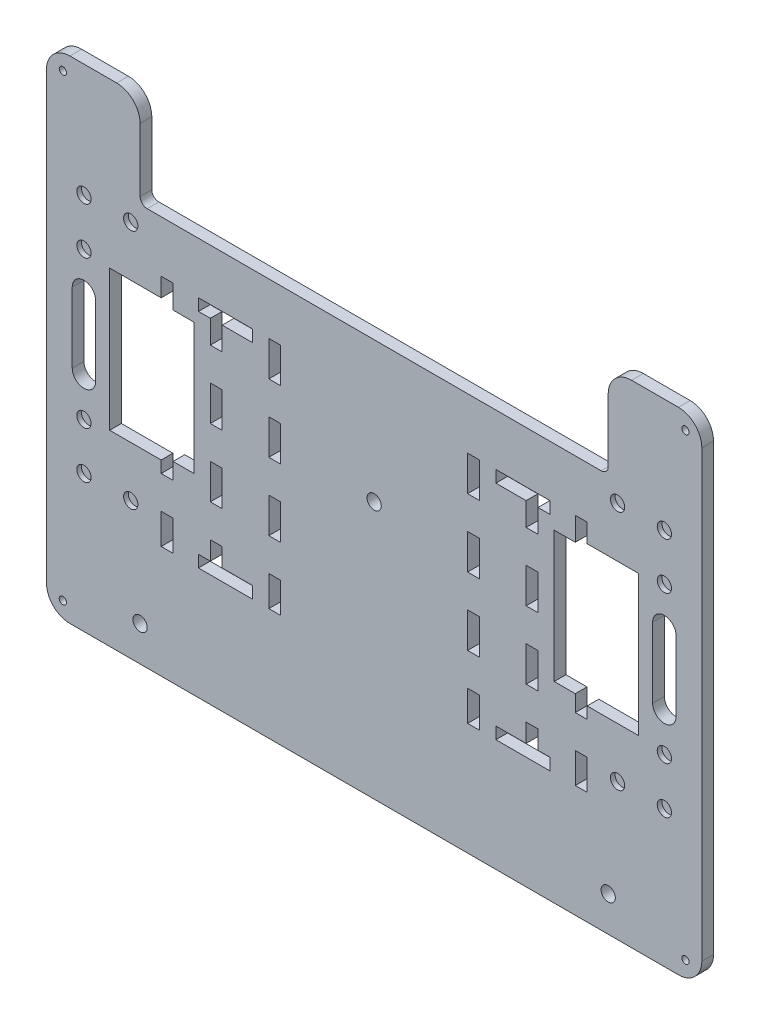
SolidWorks part; units mm, degrees
material "Acrylique (impact moyen-haut)"
ref_plane "Plan de face" through (0, 0, 0) normal (0, 0, 1) x (1, 0, 0)
ref_plane "Plan de dessus" through (0, 0, 0) normal (0, 1, 0) x (1, 0, 0)
ref_plane "Plan de droite" through (0, 0, 0) normal (1, 0, 0) x (0, 0, -1)
sketch "Esquisse1" plane through (0, 0, 0) normal (0, 0, 1) x (1, 0, 0)
  line L1 (130, -105) -> (-130, -105)
  line L2 (140, -95) -> (140, 105)
  line L3 (140, 105) -> (-140, 105)
  line L4 (-140, -95) -> (-140, 105)
  line L5 (140, -105) -> (-140, 105) construction
  line L6 (140, 105) -> (-140, -105) construction
  arc A0 (130, -105) -> (140, -95) centre (130, -95) ccw
  arc A1 (-130, -105) -> (-140, -95) centre (-130, -95) cw
  point P0 (0, 0)
  dimension "D3" = 10
  dimension "D1" = 210
  dimension "D2" = 280
extrude "Boss.-Extru.1" add sketch "Esquisse1" along normal blind 5
sketch "Esquisse2" plane through (0, 0, 5) normal (0, 0, 1) x (1, 0, 0)
  line L0 (-85.93, -1) -> (-91, -1)
  line L1 (-85.93, 28) -> (-91, 28)
  line L2 (-85.93, 28) -> (-85.93, 43)
  line L3 (-85.93, 43) -> (-91, 43)
  line L4 (-91, 28) -> (-91, 43)
  line L5 (-85.93, 28) -> (-91, 43) construction
  line L6 (-85.93, 43) -> (-91, 28) construction
  line L7 (-85.93, -1) -> (-85.93, 14)
  line L8 (-85.93, 14) -> (-91, 14)
  line L9 (-91, -1) -> (-91, 14)
  line L10 (-85.93, -1) -> (-91, 14) construction
  line L11 (-85.93, 14) -> (-91, -1) construction
  line L12 (-85.93, -57) -> (-91, -57)
  line L13 (-85.93, -30) -> (-91, -30)
  line L14 (-85.93, -30) -> (-85.93, -15)
  line L15 (-85.93, -15) -> (-91, -15)
  line L16 (-91, -30) -> (-91, -15)
  line L17 (-85.93, -30) -> (-91, -15) construction
  line L18 (-85.93, -15) -> (-91, -30) construction
  line L19 (-85.93, -57) -> (-85.93, -44)
  line L20 (-85.93, -44) -> (-91, -44)
  line L21 (-91, -57) -> (-91, -44)
  line L22 (-85.93, -57) -> (-91, -44) construction
  line L23 (-85.93, -44) -> (-91, -57) construction
  line L26 (-64.93, -1) -> (-70, -1)
  line L27 (-64.93, 28) -> (-70, 28)
  line L28 (-64.93, 28) -> (-64.93, 43)
  line L29 (-64.93, 43) -> (-70, 43)
  line L30 (-70, 28) -> (-70, 43)
  line L31 (-64.93, 28) -> (-70, 43) construction
  line L32 (-64.93, 43) -> (-70, 28) construction
  line L33 (-64.93, -1) -> (-64.93, 14)
  line L34 (-64.93, 14) -> (-70, 14)
  line L35 (-70, -1) -> (-70, 14)
  line L36 (-64.93, -1) -> (-70, 14) construction
  line L37 (-64.93, 14) -> (-70, -1) construction
  line L38 (-64.93, -57) -> (-70, -57)
  line L39 (-64.93, -30) -> (-70, -30)
  line L40 (-64.93, -30) -> (-64.93, -15)
  line L41 (-64.93, -15) -> (-70, -15)
  line L42 (-70, -30) -> (-70, -15)
  line L43 (-64.93, -30) -> (-70, -15) construction
  line L44 (-64.93, -15) -> (-70, -30) construction
  line L45 (-64.93, -57) -> (-64.93, -44)
  line L46 (-64.93, -44) -> (-70, -44)
  line L47 (-70, -57) -> (-70, -44)
  line L48 (-64.93, -57) -> (-70, -44) construction
  line L49 (-64.93, -44) -> (-70, -57) construction
  line L50 (-39.93, -1) -> (-45, -1)
  line L51 (-39.93, 28) -> (-45, 28)
  line L52 (-39.93, 28) -> (-39.93, 43)
  line L53 (-39.93, 43) -> (-45, 43)
  line L54 (-45, 28) -> (-45, 43)
  line L55 (-39.93, 28) -> (-45, 43) construction
  line L56 (-39.93, 43) -> (-45, 28) construction
  line L57 (-39.93, -1) -> (-39.93, 14)
  line L58 (-39.93, 14) -> (-45, 14)
  line L59 (-45, -1) -> (-45, 14)
  line L60 (-39.93, -1) -> (-45, 14) construction
  line L61 (-39.93, 14) -> (-45, -1) construction
  line L62 (-39.93, -57) -> (-45, -57)
  line L63 (-39.93, -30) -> (-45, -30)
  line L64 (-39.93, -30) -> (-39.93, -15)
  line L65 (-39.93, -15) -> (-45, -15)
  line L66 (-45, -30) -> (-45, -15)
  line L67 (-39.93, -30) -> (-45, -15) construction
  line L68 (-39.93, -15) -> (-45, -30) construction
  line L69 (-39.93, -57) -> (-39.93, -44)
  line L70 (-39.93, -44) -> (-45, -44)
  line L71 (-45, -57) -> (-45, -44)
  line L72 (-39.93, -57) -> (-45, -44) construction
  line L73 (-39.93, -44) -> (-45, -57) construction
  line L74 (0, 0) -> (0, 77.3847) construction
  line L75 (-75.07, 43) -> (-52, 43)
  line L76 (-75.07, 43) -> (-75.07, 37.93)
  line L77 (-75.07, 37.93) -> (-52, 37.93)
  line L78 (-52, 43) -> (-52, 37.93)
  line L79 (-75.07, -57) -> (-52, -57)
  line L80 (-75.07, -57) -> (-75.07, -51.93)
  line L81 (-75.07, -51.93) -> (-52, -51.93)
  line L82 (-52, -57) -> (-52, -51.93)
  line L83 (39.93, -44) -> (45, -57) construction
  line L84 (39.93, -57) -> (45, -44) construction
  line L85 (39.93, -15) -> (45, -30) construction
  line L86 (39.93, -30) -> (45, -15) construction
  line L87 (39.93, 14) -> (45, -1) construction
  line L88 (39.93, -1) -> (45, 14) construction
  line L89 (39.93, 43) -> (45, 28) construction
  line L90 (39.93, 28) -> (45, 43) construction
  line L91 (64.93, -44) -> (70, -57) construction
  line L92 (64.93, -57) -> (70, -44) construction
  line L93 (64.93, -15) -> (70, -30) construction
  line L94 (64.93, -30) -> (70, -15) construction
  line L95 (64.93, 14) -> (70, -1) construction
  line L96 (64.93, -1) -> (70, 14) construction
  line L97 (64.93, 43) -> (70, 28) construction
  line L98 (64.93, 28) -> (70, 43) construction
  line L99 (85.93, -44) -> (91, -57) construction
  line L100 (85.93, -57) -> (91, -44) construction
  line L101 (85.93, -15) -> (91, -30) construction
  line L102 (85.93, -30) -> (91, -15) construction
  line L103 (85.93, 14) -> (91, -1) construction
  line L104 (85.93, -1) -> (91, 14) construction
  line L105 (85.93, 43) -> (91, 28) construction
  line L106 (85.93, 28) -> (91, 43) construction
  line L107 (52, -57) -> (52, -51.93)
  line L108 (75.07, -51.93) -> (52, -51.93)
  line L109 (75.07, -57) -> (75.07, -51.93)
  line L110 (75.07, -57) -> (52, -57)
  line L111 (52, 43) -> (52, 37.93)
  line L112 (75.07, 37.93) -> (52, 37.93)
  line L113 (75.07, 43) -> (75.07, 37.93)
  line L114 (75.07, 43) -> (52, 43)
  line L115 (45, -57) -> (45, -44)
  line L116 (39.93, -44) -> (45, -44)
  line L117 (39.93, -57) -> (39.93, -44)
  line L118 (45, -30) -> (45, -15)
  line L119 (39.93, -15) -> (45, -15)
  line L120 (39.93, -30) -> (39.93, -15)
  line L121 (39.93, -30) -> (45, -30)
  line L122 (39.93, -57) -> (45, -57)
  line L123 (45, -1) -> (45, 14)
  line L124 (39.93, 14) -> (45, 14)
  line L125 (39.93, -1) -> (39.93, 14)
  line L126 (45, 28) -> (45, 43)
  line L127 (39.93, 43) -> (45, 43)
  line L128 (39.93, 28) -> (39.93, 43)
  line L129 (39.93, 28) -> (45, 28)
  line L130 (39.93, -1) -> (45, -1)
  line L131 (70, -57) -> (70, -44)
  line L132 (64.93, -44) -> (70, -44)
  line L133 (64.93, -57) -> (64.93, -44)
  line L134 (70, -30) -> (70, -15)
  line L135 (64.93, -15) -> (70, -15)
  line L136 (64.93, -30) -> (64.93, -15)
  line L137 (64.93, -30) -> (70, -30)
  line L138 (64.93, -57) -> (70, -57)
  line L139 (70, -1) -> (70, 14)
  line L140 (64.93, 14) -> (70, 14)
  line L141 (64.93, -1) -> (64.93, 14)
  line L142 (70, 28) -> (70, 43)
  line L143 (64.93, 43) -> (70, 43)
  line L144 (64.93, 28) -> (64.93, 43)
  line L145 (64.93, 28) -> (70, 28)
  line L146 (64.93, -1) -> (70, -1)
  line L147 (91, -57) -> (91, -44)
  line L148 (85.93, -44) -> (91, -44)
  line L149 (85.93, -57) -> (85.93, -44)
  line L150 (91, -30) -> (91, -15)
  line L151 (85.93, -15) -> (91, -15)
  line L152 (85.93, -30) -> (85.93, -15)
  line L153 (85.93, -30) -> (91, -30)
  line L154 (85.93, -57) -> (91, -57)
  line L155 (91, -1) -> (91, 14)
  line L156 (85.93, 14) -> (91, 14)
  line L157 (85.93, -1) -> (85.93, 14)
  line L158 (91, 28) -> (91, 43)
  line L159 (85.93, 43) -> (91, 43)
  line L160 (85.93, 28) -> (85.93, 43)
  line L161 (85.93, 28) -> (91, 28)
  line L162 (85.93, -1) -> (91, -1)
  line L163 (76.93, -23) -> (85.93, 33) construction
  line L164 (-91, -25) -> (-113, -25)
  line L165 (-91, -25) -> (-91, 35)
  line L166 (-91, 35) -> (-113, 35)
  line L167 (-113, -25) -> (-113, 35)
  line L168 (-91, -25) -> (-113, 35) construction
  line L169 (-91, 35) -> (-113, -25) construction
  line L170 (-76.93, -23) -> (-85.93, -23)
  line L171 (-76.93, -23) -> (-76.93, 33)
  line L172 (-76.93, 33) -> (-85.93, 33)
  line L173 (-85.93, -23) -> (-85.93, 33)
  line L174 (-76.93, -23) -> (-85.93, 33) construction
  line L175 (-76.93, 33) -> (-85.93, -23) construction
  line L176 (76.93, 33) -> (85.93, -23) construction
  line L177 (91, 35) -> (113, -25) construction
  line L178 (91, -25) -> (113, 35) construction
  line L179 (91, 35) -> (113, 35)
  line L180 (113, -25) -> (113, 35)
  line L181 (91, -25) -> (113, -25)
  line L182 (91, -25) -> (91, 35)
  line L183 (85.93, -23) -> (85.93, 33)
  line L184 (76.93, -23) -> (85.93, -23)
  line L185 (76.93, -23) -> (76.93, 33)
  line L186 (76.93, 33) -> (85.93, 33)
  line L187 (140, 105) -> (-140, 105) construction
  line L188 (-140, 105) -> (-140, -95) construction
  point P0 (-88.465, 35.5)
  point P5 (-88.465, 6.5)
  point P10 (-88.465, -22.5)
  point P15 (-88.465, -50.5)
  point P24 (-67.465, 35.5)
  point P29 (-67.465, 6.5)
  point P34 (-67.465, -22.5)
  point P39 (-67.465, -50.5)
  point P44 (-42.465, 35.5)
  point P49 (-42.465, 6.5)
  point P54 (-42.465, -22.5)
  point P59 (-42.465, -50.5)
  point P131 (42.465, -50.5)
  point P132 (42.465, -22.5)
  point P133 (42.465, 6.5)
  point P134 (42.465, 35.5)
  point P135 (67.465, -50.5)
  point P136 (67.465, -22.5)
  point P137 (67.465, 6.5)
  point P138 (67.465, 35.5)
  point P139 (88.465, -50.5)
  point P140 (88.465, -22.5)
  point P141 (88.465, 6.5)
  point P142 (88.465, 35.5)
  point P143 (-102, 5)
  point P148 (-81.43, 5)
  point P153 (81.43, 5)
  point P158 (102, 5)
  dimension "D1" = 5.07
  dimension "D2" = 15
  dimension "D3" = 5.07
  dimension "D4" = 14
  dimension "D5" = 0
  dimension "D6" = 15
  dimension "D7" = 5.07
  dimension "D8" = 15
  dimension "D9" = 5.07
  dimension "D10" = 14
  dimension "D11" = 0
  dimension "D12" = 100
  dimension "D13" = 14
  dimension "D14" = 0
  dimension "D15" = 100
  dimension "D16" = 27
  dimension "D17" = 5.07
  dimension "D18" = 15
  dimension "D19" = 5.07
  dimension "D20" = 14
  dimension "D21" = 0
  dimension "D22" = 15
  dimension "D23" = 5.07
  dimension "D24" = 15
  dimension "D25" = 5.07
  dimension "D26" = 14
  dimension "D27" = 0
  dimension "D28" = 14
  dimension "D29" = 0
  dimension "D30" = 100
  dimension "D31" = 0
  dimension "D32" = 46
  dimension "D33" = 5.07
  dimension "D34" = 15
  dimension "D35" = 5.07
  dimension "D36" = 14
  dimension "D37" = 0
  dimension "D38" = 15
  dimension "D39" = 5.07
  dimension "D40" = 15
  dimension "D41" = 5.07
  dimension "D42" = 14
  dimension "D43" = 0
  dimension "D44" = 14
  dimension "D45" = 0
  dimension "D46" = 100
  dimension "D47" = 0
  dimension "D48" = 25
  dimension "D49" = 23.07
  dimension "D50" = 15.93
  dimension "D51" = 5.07
  dimension "D52" = 5.07
  dimension "D53" = 23.07
  dimension "D54" = 5.07
  dimension "D55" = 5.07
  dimension "D56" = 15.93
  dimension "D57" = 0
  dimension "D58" = 60
  dimension "D59" = 22
  dimension "D60" = 38
  dimension "D61" = 38
  dimension "D62" = 56
  dimension "D63" = 0
  dimension "D64" = 9
extrude "Enlèv. mat.-Extru.1" cut sketch "Esquisse2" against normal blind 10 contours L183 L156 L182 L161 | L186 L185 L184 L152 L183 L157 L160 | L160 L161 L158 L159 | L182 L150 L181 L180 L179 L158 L155 | L157 L162 L155 L156 | L152 L153 L150 L151 | L183 L151 L182 L162 | L131 L110 L109 L108 | L133 L110 L131 L108 | L110 L133 L108 L107 | L149 L154 L147 L148 | L167 L164 L16 L165 L9 L4 L166 | L9 L0 L7 L8 | L8 L173 L1 L165 | L15 L173 L0 L165 | L77 L30 L27 L28 | L116 L115 L122 L117 | L121 L118 L119 L120 | L137 L134 L135 L136 | L141 L140 L139 L146 | L123 L124 L125 L130 | L129 L126 L127 L128 | L144 L143 L142 L145 | L112 L111 L114 L113 | L20 L21 L12 L19 | L81 L82 L79 L80 | L47 L46 L45 L38 | L71 L70 L69 L62 | L66 L65 L64 L63 | L39 L42 L41 L40 | L26 L35 L34 L33 | L50 L59 L58 L57 | L51 L54 L53 L52
sketch "Esquisse3" plane through (0, 0, 5) normal (0, 0, 1) x (1, 0, 0)
  line L0 (-124, 5) -> (-31.3779, 5) construction
  line L1 (-113, -25) -> (-113, 35) construction
  line L3 (-124, 36.5) -> (-124, -26.5) construction
  line L4 (-140, 105) -> (-140, -95) construction
  line L5 (0, 0) -> (0, 65.434) construction
  line L6 (124, 36.5) -> (124, -26.5) construction
  circle A0 centre (-124, -26.5) radius 3.05
  circle A1 centre (-124, 36.5) radius 3.05
  circle A2 centre (124, 36.5) radius 3.05
  circle A3 centre (124, -26.5) radius 3.05
  circle A4 centre (-124, 56.5) radius 3.05
  circle A5 centre (-104, 56.5) radius 3.05
  circle A6 centre (-104, -46.5) radius 3.05
  circle A7 centre (-124, -46.5) radius 3.05
  circle A8 centre (124, -46.5) radius 3.05
  circle A9 centre (104, -46.5) radius 3.05
  circle A10 centre (104, 56.5) radius 3.05
  circle A11 centre (124, 56.5) radius 3.05
  point P4 (-113, 5)
  point P5 (-124, 5)
  point P17 (124, 5)
  point P18 (113, 5)
  dimension "D1" = 6.1
  dimension "D4" = 6.1
  dimension "D6" = 6.1
  dimension "D2" = 63
  dimension "D3" = 16
  dimension "D5" = 20
  dimension "D7" = 20
extrude "Enlèv. mat.-Extru.2" cut sketch "Esquisse3" against normal blind 2
sketch "Esquisse4" plane through (0, 0, 5) normal (0, 0, 1) x (1, 0, 0)
  line L0 (-124, 20) -> (-124, -10) construction
  line L1 (-119, 20) -> (-119, -10)
  line L2 (-129, 20) -> (-129, -10)
  line L3 (-124, 36.5) -> (-124, -26.5) construction
  line L4 (0, 0) -> (0, 61.7257) construction
  line L5 (124, 36.5) -> (124, -26.5) construction
  line L6 (124, 20) -> (124, -10) construction
  line L7 (119, 20) -> (119, -10)
  line L8 (129, 20) -> (129, -10)
  line L9 (-110, 105) -> (110, 105)
  line L11 (-100, 95) -> (-100, 68)
  line L12 (-97, 65) -> (97, 65)
  line L14 (140, 105) -> (130, 105)
  line L15 (140, 95) -> (140, 105)
  line L16 (-140, 95) -> (-140, 105)
  line L17 (100, 95) -> (100, 68)
  line L18 (-140, 105) -> (-130, 105)
  arc A0 (-119, 20) -> (-129, 20) centre (-124, 20) ccw
  arc A1 (-129, -10) -> (-119, -10) centre (-124, -10) ccw
  arc A2 (119, 20) -> (129, 20) centre (124, 20) cw
  arc A3 (129, -10) -> (119, -10) centre (124, -10) cw
  arc A4 (-100, 95) -> (-110, 105) centre (-110, 95) ccw
  arc A5 (-140, 95) -> (-130, 105) centre (-130, 95) cw
  arc A6 (-100, 68) -> (-97, 65) centre (-97, 68) ccw
  arc A7 (100, 68) -> (97, 65) centre (97, 68) cw
  arc A8 (140, 95) -> (130, 105) centre (130, 95) ccw
  arc A9 (100, 95) -> (110, 105) centre (110, 95) cw
  point P2 (-124, 5)
  point P18 (124, 5)
  point P40 (-140, 105)
  point P43 (-100, 65)
  point P50 (100, 65)
  dimension "D4" = 10
  dimension "D5" = 10
  dimension "D6" = 3
  dimension "D1" = 10
  dimension "D2" = 30
  dimension "D3" = 194
  dimension "D7" = 40
  dimension "D8" = 220
extrude "Enlèv. mat.-Extru.3" cut sketch "Esquisse4" against normal through all
sketch "Esquisse5" plane through (0, 0, 5) normal (0, 0, 1) x (1, 0, 0)
  line L0 (-119, 5) -> (119, 5) construction
  line L1 (-119, -10) -> (-119, 20) construction
  line L2 (119, 20) -> (119, -10) construction
  line L3 (-140, 95) -> (-140, -95) construction
  line L4 (-110, 105) -> (-130, 105) construction
  line L5 (-130, -105) -> (130, -105) construction
  line L6 (0, 5) -> (0, 82.0623) construction
  circle A0 centre (0, 5) radius 3.05
  circle A1 centre (-133, 98) radius 1.55
  circle A2 centre (-100, -90) radius 3.05
  circle A3 centre (-133, -98) radius 1.55
  circle A4 centre (133, -98) radius 1.55
  circle A5 centre (100, -90) radius 3.05
  circle A6 centre (133, 98) radius 1.55
  point P6 (0, 5)
  dimension "D1" = 6.1
  dimension "D2" = 3.1
  dimension "D5" = 6.1
  dimension "D8" = 3.1
  dimension "D9" = 7
  dimension "D3" = 7
  dimension "D4" = 7
  dimension "D6" = 40
  dimension "D7" = 15
  dimension "D10" = 7
extrude "Enlèv. mat.-Extru.4" cut sketch "Esquisse5" against normal through all
